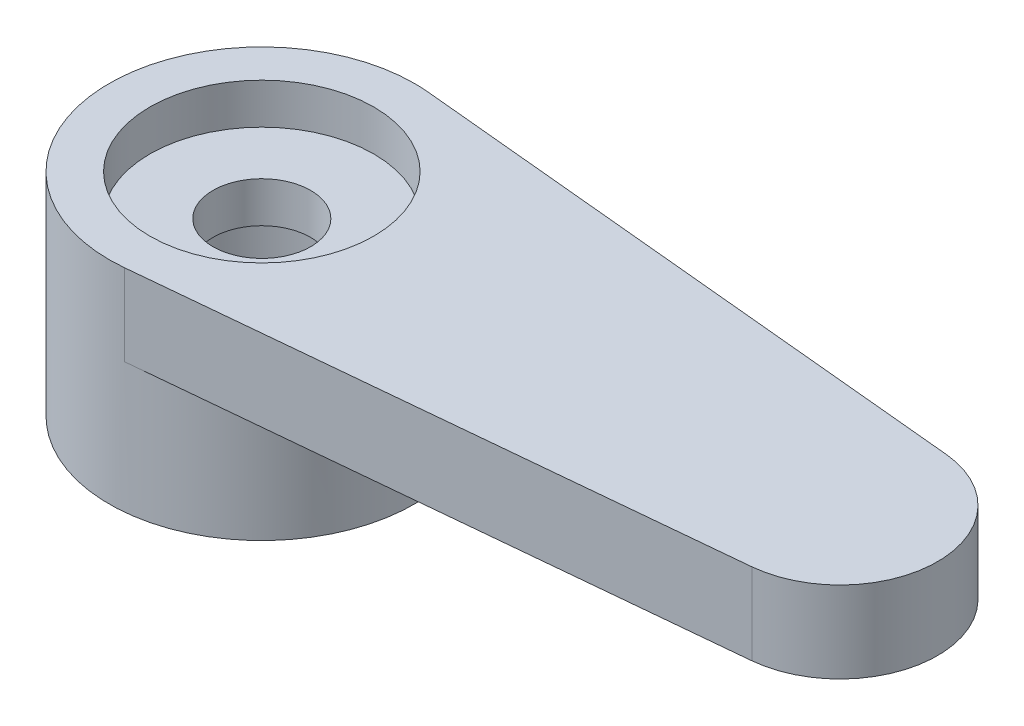
SolidWorks part; units mm, degrees
ref_plane "Front Plane" through (0, 0, 0) normal (0, 0, 1) x (1, 0, 0)
ref_plane "Top Plane" through (0, 0, 0) normal (0, 1, 0) x (1, 0, 0)
ref_plane "Right Plane" through (0, 0, 0) normal (1, 0, 0) x (0, 0, -1)
sketch "Sketch1" plane through (0, 0, 0) normal (0, 1, 0) x (1, 0, 0)
  line L0 (0, 0) -> (14.2, 0) construction
  line L1 (0.3565, 3.733) -> (14.4282, 2.3891)
  line L2 (0.3565, -3.733) -> (14.4282, -2.3891)
  arc A0 (0.3565, 3.733) -> (0.3565, -3.733) centre (0, 0) ccw
  arc A1 (14.4282, -2.3891) -> (14.4282, 2.3891) centre (14.2, 0) ccw
  circle A2 centre (0, 0) radius 1.2
  dimension "D1" = 7.5
  dimension "D3" = 4.8
  dimension "D4" = 2.4
  dimension "D2" = 14.2
extrude "Boss-Extrude1" add sketch "Sketch1" along normal blind 2
sketch "Sketch2" plane through (0, 0, 0) normal (0, -1, 0) x (1, 0, 0)
  line L2 (14.4282, 2.3891) -> (0.3565, 3.733)
  line L3 (0.3565, -3.733) -> (14.4282, -2.3891)
  line L4 (14.4282, 2.3891) -> (0.3565, 3.733)
  line L5 (0.3565, -3.733) -> (14.4282, -2.3891)
  circle A0 centre (0, 0) radius 3.75
  circle A1 centre (0, 0) radius 1.2
  arc A2 (14.4282, -2.3891) -> (14.4282, 2.3891) centre (14.2, 0) ccw
  arc A3 (0.3565, 3.733) -> (0.3565, -3.733) centre (0, 0) ccw
  arc A4 (14.4282, -2.3891) -> (14.4282, 2.3891) centre (14.2, 0) ccw
  arc M7 (0.3565, 3.733) -> (0.3565, -3.733) centre (0, 0) ccw
  circle M9 centre (0, 0) radius 1.2
  dimension "D1" = 0
extrude "Boss-Extrude2" add sketch "Sketch2" along normal blind 3.2 contours A0 M7 M9
sketch "Sketch3" plane through (0, -3.2, 0) normal (0, -1, 0) x (1, 0, 0)
  circle A0 centre (0, 0) radius 2.4
  dimension "D1" = 4.8
extrude "Cut-Extrude3" cut sketch "Sketch3" against normal up to surface (3.2 mm away) up to face at (8.7837, 0, 0)
sketch "Sketch4" plane through (0, 2, 0) normal (0, 1, 0) x (1, 0, 0)
  circle A0 centre (0, 0) radius 2.75
  dimension "D1" = 5.5
extrude "Cut-Extrude4" cut sketch "Sketch4" against normal blind 1
